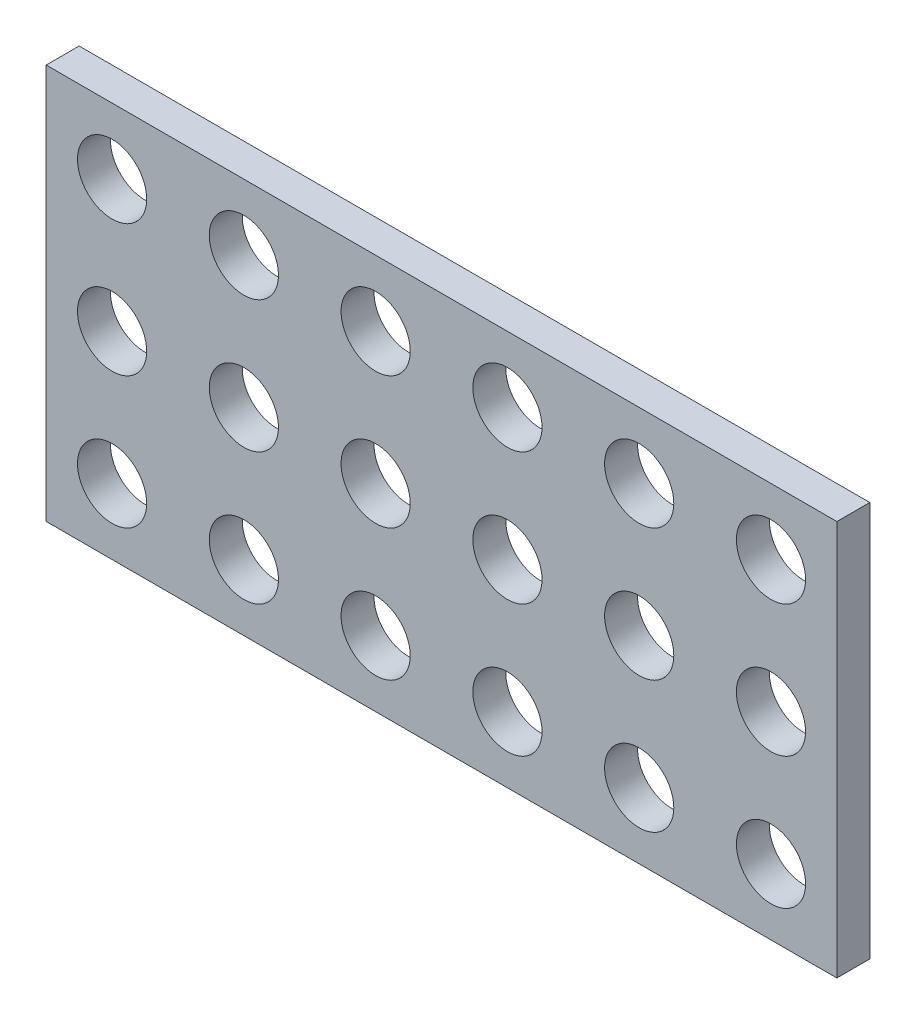
SolidWorks part; units mm, degrees
material "Alliage 6061"
ref_plane "Face" through (0, 0, 0) normal (0, 0, 1) x (1, 0, 0)
ref_plane "Dessus" through (0, 0, 0) normal (0, 1, 0) x (1, 0, 0)
ref_plane "Droite" through (0, 0, 0) normal (1, 0, 0) x (0, 0, -1)
sketch "Esquisse1" plane through (0, 0, 0) normal (0, 0, 1) x (1, 0, 0)
  line L1 (0, 24) -> (48, 24)
  line L2 (0, 24) -> (0, 0)
  line L3 (0, 0) -> (48, 0)
  line L4 (48, 24) -> (48, 0)
  dimension "D1" = 48
  dimension "D2" = 24
extrude "Boss.-Extru.1" add sketch "Esquisse1" along normal blind 2
sketch "Esquisse2" plane through (0, 0, 2) normal (0, 0, 1) x (1, 0, 0)
  line L0 (48, 24) -> (0, 24) construction
  line L1 (0, 24) -> (0, 0) construction
  circle A0 centre (4, 20) radius 2.1
  dimension "D1" = 4.2
  dimension "D2" = 4
  dimension "D3" = 4
extrude "Enlèv. mat.-Extru.1" cut sketch "Esquisse2" against normal through all
pattern_linear "Répétition linéaire1" count 3 spacing 8 along (0, -1, 0) count 6 spacing 8 along (1, 0, 0) of "Enlèv. mat.-Extru.1"
